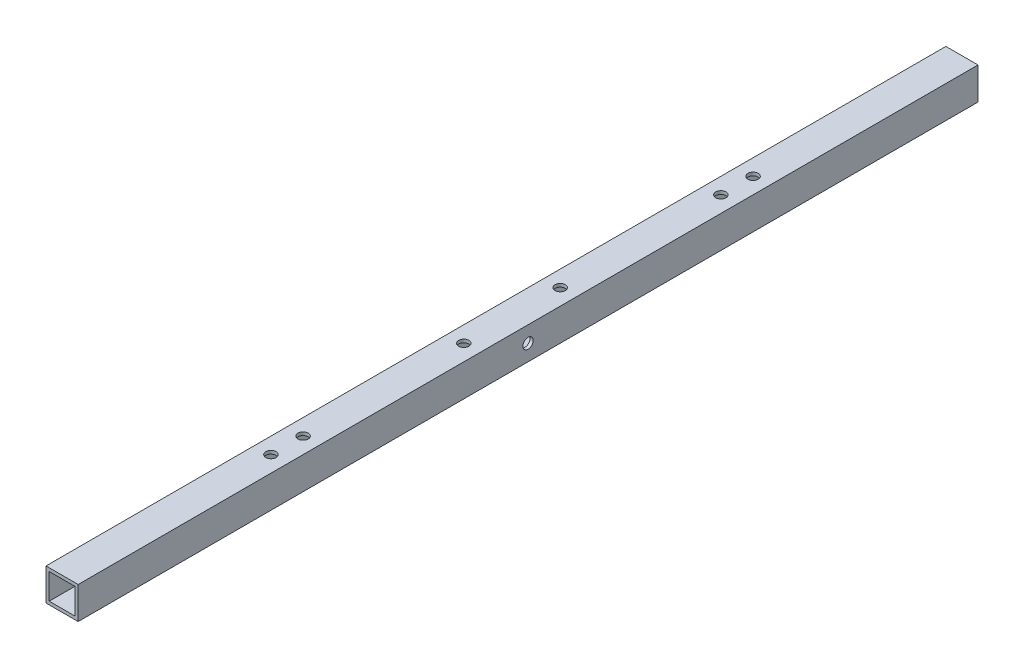
SolidWorks part; units mm, degrees
ref_plane "正面" through (0, 0, 0) normal (0, 0, 1) x (1, 0, 0)
ref_plane "平面" through (0, 0, 0) normal (0, 1, 0) x (1, 0, 0)
ref_plane "右側面" through (0, 0, 0) normal (1, 0, 0) x (0, 0, -1)
sketch "Sketch1" plane through (0, 0, 0) normal (0, 0, 1) x (1, 0, 0)
  line L1 (-5, 5) -> (5, 5)
  line L2 (-5, 5) -> (-5, -5)
  line L3 (-5, -5) -> (5, -5)
  line L4 (5, 5) -> (5, -5)
  line L5 (-5, 5) -> (5, -5) construction
  line L6 (-5, -5) -> (5, 5) construction
  line L7 (-4, 4) -> (4, 4)
  line L8 (-4, 4) -> (-4, -4)
  line L9 (-4, -4) -> (4, -4)
  line L10 (4, 4) -> (4, -4)
  line L11 (-4, 4) -> (4, -4) construction
  line L12 (-4, -4) -> (4, 4) construction
  point P0 (0, 0)
  point P6 (0, 0)
  dimension "D1" = 10
  dimension "D2" = 10
  dimension "D3" = 8
extrude "Boss-Extrude1" add sketch "Sketch1" along normal blind 280
sketch "Sketch2" plane through (5, 0, 0) normal (1, 0, 0) x (0, 0, -1)
  line L0 (-280, 0) -> (0, 0) construction
  line L1 (-280, -5) -> (-280, 5) construction
  circle A0 centre (-140, 0) radius 1.6
  dimension "D1" = 3.2
extrude "Cut-Extrude1" cut sketch "Sketch2" against normal up to surface (10 mm away) up to face at (-5, 0, 140)
sketch "Sketch3" plane through (0, 5, 0) normal (0, 1, 0) x (1, 0, 0)
  line L0 (0, 0) -> (0, -280) construction
  line L1 (5, -280) -> (-5, -280) construction
  line L2 (-5, -140) -> (5, -140) construction
  line L3 (-5, -280) -> (-5, 0) construction
  line L4 (5, -280) -> (5, 0) construction
  line L5 (-5, -55) -> (5, -55) construction
  circle A0 centre (0, -65) radius 1.6
  circle A1 centre (0, -75) radius 1.6
  circle A2 centre (0, -205) radius 1.6
  circle A3 centre (0, -215) radius 1.6
  circle A4 centre (0, -125) radius 1.6
  circle A5 centre (0, -155) radius 1.6
  dimension "D2" = 3.2
  dimension "D6" = 3.2
  dimension "D1" = 85
  dimension "D3" = 10
  dimension "D4" = 10
  dimension "D5" = 15
extrude "Cut-Extrude2" cut sketch "Sketch3" against normal up to surface (10 mm away) up to face at (0, -5, 140)
